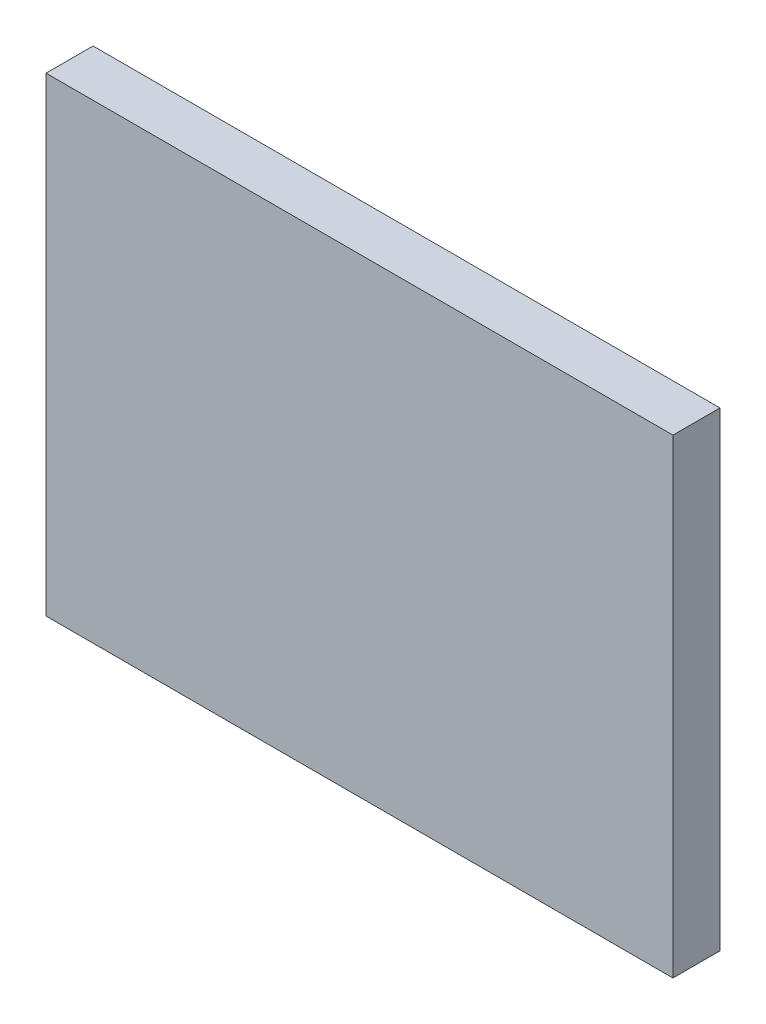
SolidWorks part; units mm, degrees
ref_plane "前视基准面" through (0, 0, 0) normal (0, 0, 1) x (1, 0, 0)
ref_plane "上视基准面" through (0, 0, 0) normal (0, 1, 0) x (1, 0, 0)
ref_plane "右视基准面" through (0, 0, 0) normal (1, 0, 0) x (0, 0, -1)
other "Configuration Table"
sketch "草图1" plane through (0, 0, 0) normal (0, 0, 1) x (1, 0, 0)
  line L1 (-20, -15) -> (20, -15)
  line L2 (-20, -15) -> (-20, 15)
  line L3 (-20, 15) -> (20, 15)
  line L4 (20, -15) -> (20, 15)
extrude "凸台-拉伸1" add sketch "草图1" along normal blind 3 separate body
sketch "草图2" plane through (0, 0, 0) normal (0, 0, 1) x (1, 0, 0)
  circle A0 centre (0, 0) radius 4
